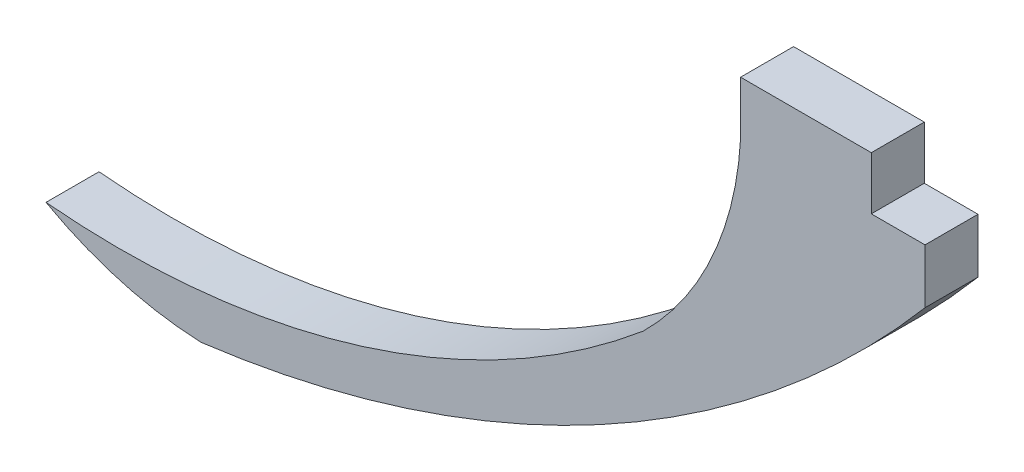
SolidWorks part; units mm, degrees
ref_plane "Front Plane" through (0, 0, 0) normal (0, 0, 1) x (1, 0, 0)
ref_plane "Top Plane" through (0, 0, 0) normal (0, 1, 0) x (1, 0, 0)
ref_plane "Right Plane" through (0, 0, 0) normal (1, 0, 0) x (0, 0, -1)
sketch "Sketch1" plane through (0, 0, 0) normal (0, 0, 1) x (1, 0, 0)
  line L0 (1.508, 1.524) -> (1.508, 0)
  line L1 (1.508, 0) -> (3.0524, 0)
  line L2 (3.0524, 0) -> (3.0524, -1.5663)
  line L4 (-2.252, 0) -> (-2.252, 1.524)
  line L5 (-2.252, 1.524) -> (1.508, 1.524)
  arc A0 (3.0524, -1.5663) -> (-17.7694, -12.839) centre (-21.8571, 19.5776) cw
  arc A1 (-22.2285, -11.5818) -> (-17.7694, -12.839) centre (-17.356, -2.8365) ccw
  arc A2 (-22.2285, -11.5818) -> (-5.0537, -6.2024) centre (-20.0849, 11.6812) ccw
  arc A3 (-2.252, 0) -> (-5.0537, -6.2024) centre (-11.6298, 0.5019) cw
extrude "Boss-Extrude1" add sketch "Sketch1" along normal blind 1.524
